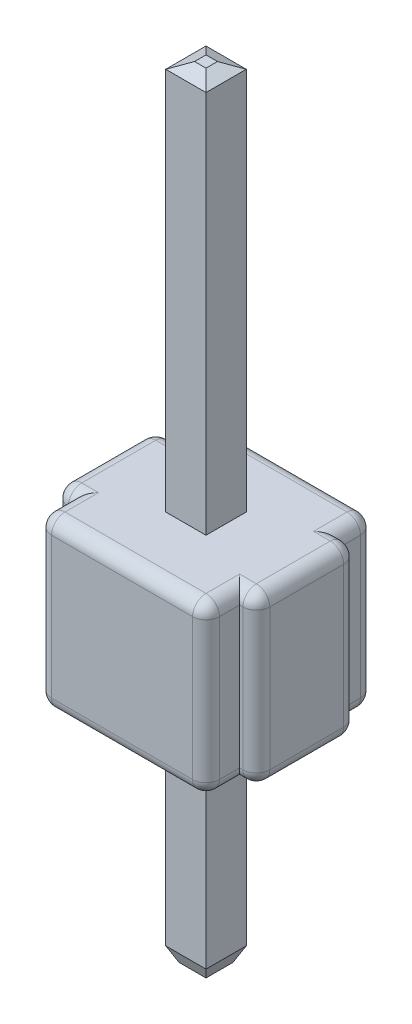
SolidWorks part; units mm, degrees
ref_plane "Front Plane" through (0, 0, 0) normal (0, 0, 1) x (1, 0, 0)
ref_plane "Top Plane" through (0, 0, 0) normal (0, 1, 0) x (1, 0, 0)
ref_plane "Right Plane" through (0, 0, 0) normal (1, 0, 0) x (0, 0, -1)
sketch "Sketch1" plane through (0, 0, 0) normal (0, 1, 0) x (1, 0, 0)
  line L0 (1.25, 0.75) -> (1.5, 0.75)
  line L1 (-1.25, 1.25) -> (1.25, 1.25)
  line L2 (-1.25, 1.25) -> (-1.25, 0.75)
  line L3 (-1.25, -1.25) -> (1.25, -1.25)
  line L4 (1.25, 1.25) -> (1.25, 0.75)
  line L5 (1.5, 0.75) -> (1.5, -0.75)
  line L6 (-1.25, 0.75) -> (-1.5, 0.75)
  line L7 (-1.5, 0.75) -> (-1.5, -0.75)
  line L8 (-1.5, -0.75) -> (-1.25, -0.75)
  line L9 (1.25, -0.75) -> (1.5, -0.75)
  line L10 (1.25, -0.75) -> (1.25, -1.25)
  line L11 (-1.25, -0.75) -> (-1.25, -1.25)
  point P6 (0, 1.25)
  point P13 (-1.5, 0)
  dimension "D1" = 0.25
  dimension "D2" = 1.5
  dimension "D3" = 2.5
  dimension "D4" = 2.5
extrude "Boss-Extrude1" add sketch "Sketch1" along normal blind 2.5
fillet "Fillet1" radius 0.2 32 edges at (-1.25, 1.25, 1.25) (1.25, 1.25, 1.25) (1.25, 1.25, -1.25) (-1.25, 1.25, -1.25) (1.5, 1.25, 0.75) (1.5, 1.25, -0.75) (-1.375, 0, -0.75) (-1.5, 0, 0) (-1.375, 0, 0.75) (-1.25, 0, 1) (0, 0, 1.25) (1.25, 0, 1) (1.375, 0, 0.75) (1.5, 0, 0) (1.375, 0, -0.75) (1.25, 0, -1) (0, 0, -1.25) (-1.25, 0, -1) (0, 2.5, -1.25) (1.25, 2.5, -1) (1.375, 2.5, -0.75) (1.5, 2.5, 0) (1.375, 2.5, 0.75) (1.25, 2.5, 1) (0, 2.5, 1.25) (-1.25, 2.5, 1) (-1.375, 2.5, 0.75) (-1.5, 2.5, 0) (-1.375, 2.5, -0.75) (-1.25, 2.5, -1) (-1.5, 1.25, -0.75) (-1.5, 1.25, 0.75)
sketch "Sketch2" plane through (0, 2.5, 0) normal (0, 1, 0) x (1, 0, 0)
  line L0 (0, 1.9006) -> (0, -2.3221) construction
  line L1 (-0.3, 0.3) -> (0.3, 0.3)
  line L2 (-0.3, 0.3) -> (-0.3, -0.3)
  line L3 (-0.3, -0.3) -> (0.3, -0.3)
  line L4 (0.3, 0.3) -> (0.3, -0.3)
  line L5 (-2.2197, 0) -> (2.4163, 0) construction
  point P4 (0, 0.3)
  point P10 (0.3, 0)
  dimension "D1" = 0.6
  dimension "D2" = 0.6
extrude "Boss-Extrude2" add sketch "Sketch2" along normal mid plane 11.62
chamfer "Chamfer1" distance 0.1 angle 65 8 edges at (0, 8.31, -0.3) (0.3, 8.31, 0) (0, 8.31, 0.3) (-0.3, 8.31, 0) (0, -3.31, 0.3) (0.3, -3.31, 0) (0, -3.31, -0.3) (-0.3, -3.31, 0)
